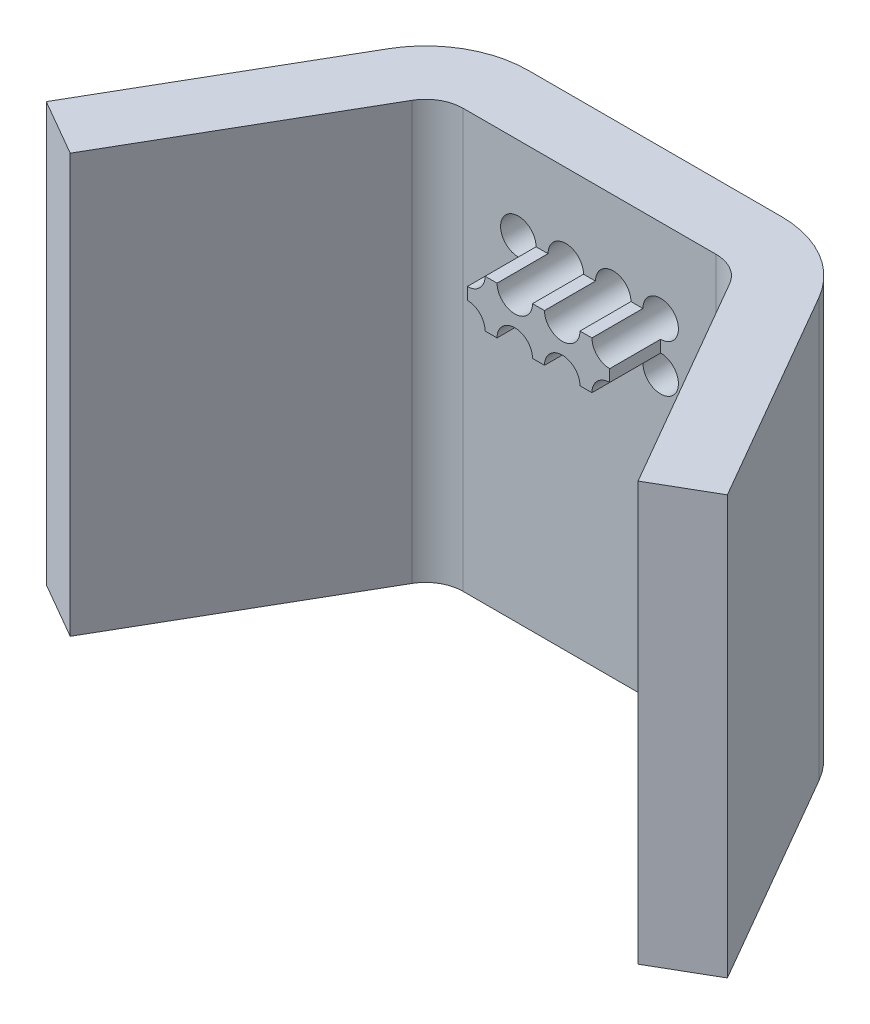
SolidWorks part; units mm, degrees
ref_plane "Front Plane" through (0, 0, 0) normal (0, 0, 1) x (1, 0, 0)
ref_plane "Top Plane" through (0, 0, 0) normal (0, 1, 0) x (1, 0, 0)
ref_plane "Right Plane" through (0, 0, 0) normal (1, 0, 0) x (0, 0, -1)
sketch "Sketch1" plane through (0, 0, 0) normal (0, 1, 0) x (1, 0, 0)
  line L5 (-7.9254, 7.9254) -> (-15.2, -4.6746)
  line L12 (-7.9254, -7.9254) -> (7.9254, -7.9254) construction
  line L13 (-7.9254, -7.9254) -> (-7.9254, 7.9254) construction
  line L14 (-7.9254, 7.9254) -> (7.9254, 7.9254)
  line L15 (7.9254, -7.9254) -> (7.9254, 7.9254) construction
  line L16 (-7.9254, -7.9254) -> (7.9254, 7.9254) construction
  line L17 (-7.9254, 7.9254) -> (7.9254, -7.9254) construction
  line L18 (-15.2, -4.6746) -> (-18.2311, -2.9246)
  line L19 (-18.2311, -2.9246) -> (-9.9461, 11.4254)
  line L24 (0, -0.303) -> (0, 16506.3789) construction
  line L25 (-9.9461, 11.4254) -> (9.9461, 11.4254)
  line L26 (-15.2, -4.6746) -> (-22.4746, -17.2746) construction
  line L27 (7.9254, 7.9254) -> (15.2, -4.6746)
  line L28 (15.2, -4.6746) -> (18.2311, -2.9246)
  line L29 (18.2311, -2.9246) -> (9.9461, 11.4254)
  point P0 (0, 0)
  point P19 (0, 11.4254)
  dimension "D1" = 15.2
  dimension "D2" = 25.2
  dimension "D3" = 3.5
  dimension "D4" = 3.5
  dimension "D5" = 60
extrude "Boss-Extrude1" add sketch "Sketch1" along normal blind 22.4
fillet "Fillet1" radius 2 2 edges at (7.9254, 11.2, -7.9254) (-7.9254, 11.2, -7.9254)
sketch "Sketch2" plane through (0, 0, -7.9254) normal (0, 0, 1) x (1, 0, 0)
  line L0 (-6.7707, 0) -> (6.7707, 0) construction
  line L1 (-3.81, 15.39) -> (3.81, 15.39) construction
  line L2 (-3.81, 15.39) -> (-3.81, 17.93) construction
  line L3 (-3.81, 17.93) -> (3.81, 17.93) construction
  line L4 (3.81, 15.39) -> (3.81, 17.93) construction
  line L5 (-3.81, 15.39) -> (3.81, 17.93) construction
  line L6 (-3.81, 17.93) -> (3.81, 15.39) construction
  line L7 (-1.27, 15.39) -> (1.27, 15.39) construction
  line L8 (-1.27, 15.39) -> (-1.27, 17.93) construction
  line L9 (-1.27, 17.93) -> (1.27, 17.93) construction
  line L10 (1.27, 15.39) -> (1.27, 17.93) construction
  line L11 (-1.27, 15.39) -> (1.27, 17.93) construction
  line L12 (-1.27, 17.93) -> (1.27, 15.39) construction
  line L18 (-0.32, 17.93) -> (0.32, 17.93)
  line L19 (2.22, 17.93) -> (2.86, 17.93)
  line L23 (-3.81, 16.98) -> (-3.81, 16.34)
  line L24 (3.81, 16.98) -> (3.81, 16.34)
  line L25 (-2.86, 17.93) -> (-2.22, 17.93)
  line L26 (2.22, 15.39) -> (2.86, 15.39)
  line L27 (-0.32, 15.39) -> (0.32, 15.39)
  line L28 (-2.86, 15.39) -> (-2.22, 15.39)
  arc A12 (-2.22, 17.93) -> (-0.32, 17.93) centre (-1.27, 17.93) ccw
  arc A13 (0.32, 17.93) -> (2.22, 17.93) centre (1.27, 17.93) ccw
  arc A14 (-2.86, 17.93) -> (-3.81, 16.98) centre (-3.81, 17.93) cw
  arc A15 (-3.81, 16.34) -> (-2.86, 15.39) centre (-3.81, 15.39) cw
  arc A16 (-2.22, 15.39) -> (-0.32, 15.39) centre (-1.27, 15.39) cw
  arc A17 (0.32, 15.39) -> (2.22, 15.39) centre (1.27, 15.39) cw
  arc A18 (3.81, 16.34) -> (2.86, 15.39) centre (3.81, 15.39) ccw
  arc A19 (3.81, 16.98) -> (2.86, 17.93) centre (3.81, 17.93) cw
  point P0 (0, 16.66)
  point P5 (0, 16.66)
  point P12 (0, 16.66)
  dimension "D6" = 0.95
  dimension "D1" = 2.54
  dimension "D2" = 2.54
  dimension "D3" = 2.54
  dimension "D4" = 15.39
fillet "Fillet2" radius 5.5 2 edges at (9.9461, 11.2, -11.4254) (-9.9461, 11.2, -11.4254)
extrude "Boss-Extrude2" add sketch "Sketch2" along normal blind 2.73
sketch "Sketch3" plane through (0, 0, -7.9254) normal (0, 0, 1) x (1, 0, 0)
  arc A0 (-2.86, 15.39) -> (-3.81, 16.34) centre (-3.81, 15.39) ccw construction
  arc A1 (-0.32, 15.39) -> (-2.22, 15.39) centre (-1.27, 15.39) ccw construction
  arc A2 (2.22, 15.39) -> (0.32, 15.39) centre (1.27, 15.39) ccw construction
  arc A3 (2.86, 17.93) -> (3.81, 16.98) centre (3.81, 17.93) ccw construction
  arc A4 (0.32, 17.93) -> (2.22, 17.93) centre (1.27, 17.93) ccw construction
  arc A5 (-3.81, 16.98) -> (-2.86, 17.93) centre (-3.81, 17.93) ccw construction
  arc A6 (-2.22, 17.93) -> (-0.32, 17.93) centre (-1.27, 17.93) ccw construction
  arc A7 (-2.86, 15.39) -> (-3.81, 16.34) centre (-3.81, 15.39) ccw construction
  arc A8 (-0.32, 15.39) -> (-2.22, 15.39) centre (-1.27, 15.39) ccw construction
  arc A9 (2.22, 15.39) -> (0.32, 15.39) centre (1.27, 15.39) ccw construction
  arc A10 (2.86, 17.93) -> (3.81, 16.98) centre (3.81, 17.93) ccw construction
  arc A11 (0.32, 17.93) -> (2.22, 17.93) centre (1.27, 17.93) ccw construction
  arc A12 (-3.81, 16.98) -> (-2.86, 17.93) centre (-3.81, 17.93) ccw construction
  arc A13 (-2.22, 17.93) -> (-0.32, 17.93) centre (-1.27, 17.93) ccw construction
  arc A14 (3.81, 16.34) -> (2.86, 15.39) centre (3.81, 15.39) ccw construction
  arc A15 (3.81, 16.34) -> (2.86, 15.39) centre (3.81, 15.39) ccw construction
  circle A16 centre (-3.81, 17.93) radius 0.95
  circle A17 centre (-1.27, 17.93) radius 0.95
  circle A18 centre (1.27, 17.93) radius 0.95
  circle A19 centre (3.81, 17.93) radius 0.95
  circle A20 centre (3.81, 15.39) radius 0.95
  circle A21 centre (1.27, 15.39) radius 0.95
  circle A22 centre (-1.27, 15.39) radius 0.95
  circle A23 centre (-3.81, 15.39) radius 0.95
extrude "Cut-Extrude2" cut sketch "Sketch3" against normal through all both and the other way through all
equation "\"tolerance\"= 0.2mm"
equation "\"D2@Sketch1\"=\"tolerance\" + 25"
equation "\"D1@Sketch1\"=\"tolerance\" + 15"
equation "\"D1@Boss-Extrude2\"=2.73 - \"tolerance\""
equation "\"D6@Sketch2\"=((\"tolerance\" * 2) + 1.5) / 2"
